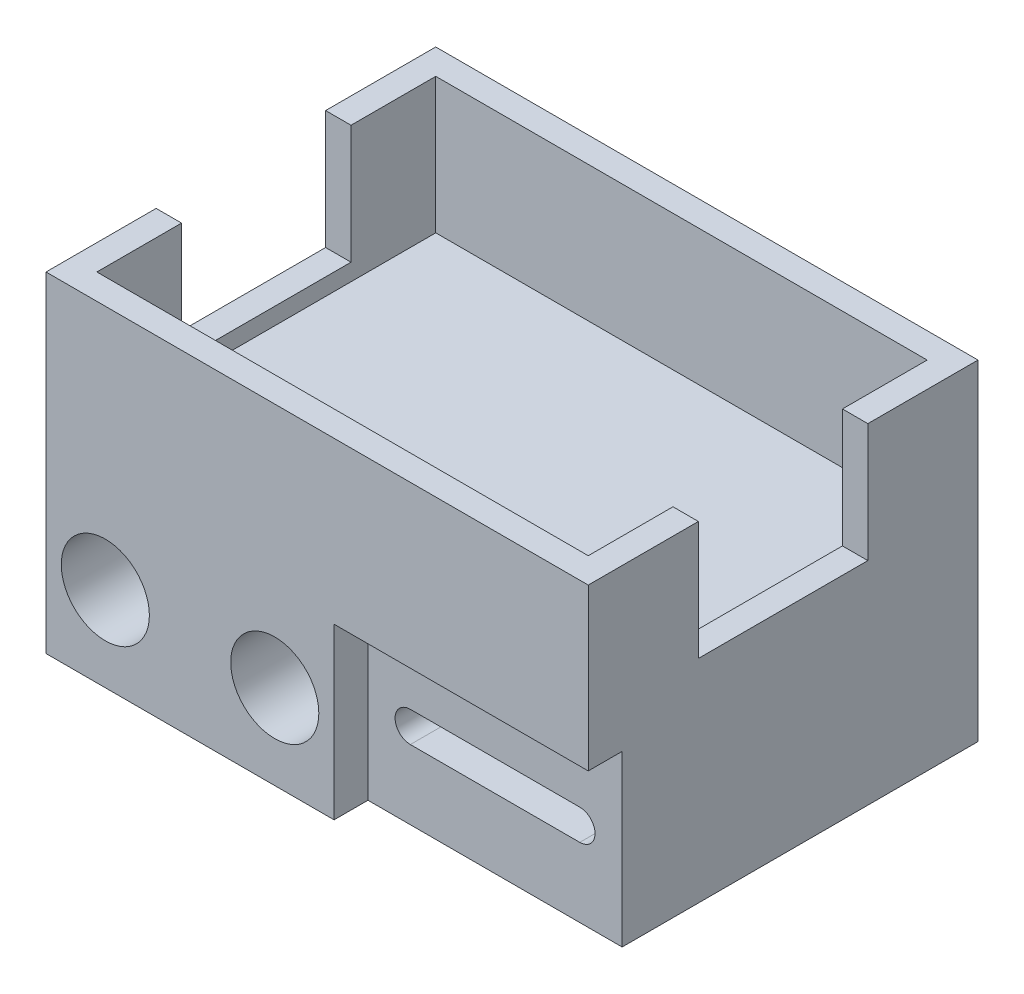
SolidWorks part; units mm, degrees
ref_plane "Front Plane" through (0, 0, 0) normal (0, 0, 1) x (1, 0, 0)
ref_plane "Top Plane" through (0, 0, 0) normal (0, 1, 0) x (1, 0, 0)
ref_plane "Right Plane" through (0, 0, 0) normal (1, 0, 0) x (0, 0, -1)
sketch "Sketch4" plane through (0, 0, 0) normal (0, 1, 0) x (1, 0, 0)
  line L1 (-16, -11.5) -> (16, -11.5)
  line L2 (-16, -11.5) -> (-16, 11.5)
  line L3 (-16, 11.5) -> (16, 11.5)
  line L4 (16, -11.5) -> (16, 11.5)
  line L5 (-16, -11.5) -> (16, 11.5) construction
  line L6 (-16, 11.5) -> (16, -11.5) construction
  point P0 (0, 0)
  dimension "D1" = 32
  dimension "D2" = 23
extrude "Boss-Extrude3" add sketch "Sketch4" along normal blind 9.5
sketch "Sketch5" plane through (0, 9.5, 0) normal (0, 1, 0) x (1, 0, 0)
  line L1 (-14.5, -10) -> (14.5, -10)
  line L2 (-14.5, -10) -> (-14.5, 10)
  line L3 (-14.5, 10) -> (14.5, 10)
  line L4 (14.5, -10) -> (14.5, 10)
  line L5 (-14.5, -10) -> (14.5, 10) construction
  line L6 (-14.5, 10) -> (14.5, -10) construction
  point P0 (0, 0)
  dimension "D1" = 29
  dimension "D2" = 20
extrude "Cut-Extrude2" cut sketch "Sketch5" against normal blind 8
sketch "Sketch7" plane through (16, 0, 0) normal (1, 0, 0) x (0, 0, -1)
  line L1 (-5, 2.5) -> (5, 2.5)
  line L2 (-5, 2.5) -> (-5, 9.5)
  line L3 (-5, 9.5) -> (5, 9.5)
  line L4 (5, 2.5) -> (5, 9.5)
  line L5 (-11.5, 9.5) -> (11.5, 9.5) construction
  point P6 (0, 9.5)
  point P8 (0, 9.5)
  dimension "D1" = 10
  dimension "D2" = 7
extrude "Cut-Extrude4" cut sketch "Sketch7" against normal through all
sketch "Sketch8" plane through (0, 0, 0) normal (0, -1, 0) x (-1, 0, 0)
  line L0 (-16, -9.5) -> (-1, -9.5)
  line L1 (-16, -11.5) -> (-16, 11.5) construction
  line L2 (-1, -9.5) -> (-1, -11.5)
  line L3 (16, -11.5) -> (-16, -11.5) construction
  line L4 (-1, -11.5) -> (16, -11.5)
  line L5 (16, -11.5) -> (16, 9.5)
  line L6 (16, 11.5) -> (16, -11.5) construction
  line L7 (16, 9.5) -> (1, 9.5)
  line L8 (1, 9.5) -> (1, 11.5)
  line L9 (-16, 11.5) -> (16, 11.5) construction
  line L10 (1, 11.5) -> (-16, 11.5)
  line L11 (-16, 11.5) -> (-16, -9.5)
  dimension "D1" = 2
  dimension "D2" = 15
extrude "Boss-Extrude4" add sketch "Sketch8" along normal blind 10
sketch "Sketch9" plane through (0, 0, -9.5) normal (0, 0, -1) x (-1, 0, 0)
  line L0 (3.5, -5) -> (13.5, -5) construction
  line L1 (3.5, -4.1) -> (13.5, -4.1)
  line L2 (3.5, -5.9) -> (13.5, -5.9)
  line L3 (16, -10) -> (1, -10) construction
  line L4 (16, -10) -> (16, 0) construction
  arc A0 (3.5, -4.1) -> (3.5, -5.9) centre (3.5, -5) ccw
  arc A1 (13.5, -5.9) -> (13.5, -4.1) centre (13.5, -5) ccw
  point P2 (8.5, -5)
  point P10 (8.5, -10)
  point P15 (16, -5)
  dimension "D1" = 1.8
  dimension "D2" = 10
ref_plane "Plane1" through (0, 0, 0) normal (0, 0, -1) x (-1, 0, 0)
extrude "Cut-Extrude5" cut sketch "Sketch9" against normal blind 5
sketch "Sketch10" plane through (0, -10, 0) normal (0, -1, 0) x (-1, 0, 0)
  line L0 (-16, 11.5) -> (-16, -9.5) construction
  line L1 (-1, -5.5) -> (-15, -5.5)
  line L2 (-1, -5.5) -> (-1, -2.5)
  line L3 (-1, -2.5) -> (-15, -2.5)
  line L4 (-15, -5.5) -> (-15, -2.5)
  line L5 (-1, -9.5) -> (-1, -11.5) construction
  line L6 (-16, -9.5) -> (-1, -9.5) construction
  line L7 (-5.5, 1) -> (-5.5, 15) [skipped]
  line L8 (-5.5, 1) -> (-2.5, 1) [skipped]
  line L9 (-2.5, 1) -> (-2.5, 15) [skipped]
  line L10 (-5.5, 15) -> (-2.5, 15) [skipped]
  line L11 (1, 5.5) -> (15, 5.5)
  line L12 (1, 5.5) -> (1, 2.5)
  line L13 (1, 2.5) -> (15, 2.5)
  line L14 (15, 5.5) -> (15, 2.5)
  line L15 (5.5, -1) -> (5.5, -15) [skipped]
  line L16 (5.5, -1) -> (2.5, -1) [skipped]
  line L17 (2.5, -1) -> (2.5, -15) [skipped]
  line L18 (5.5, -15) -> (2.5, -15) [skipped]
  line L19 (0, 0) -> (-1, -2.5) construction
  line L20 (10.725, 0) -> (-10.725, 0) construction
  point P10 (0.2818, 0)
  point P11 (0, 0)
  point P27 (-0.1187, 0)
  point P30 (2.5877, 0)
  point P32 (0, 0)
  dimension "D1" = 3
  dimension "D2" = 1
  dimension "D3" = 4
  dimension "D4" = 4
extrude "Cut-Extrude6" cut sketch "Sketch10" against normal offset from surface (7.9 mm away) 2 up to face at (-8.5, -4.1, -7) offset beyond the face yes
ref_axis "Axis1" through (0, 0, 0) along (0, -1, 0)
pattern_circular "CirPattern1" count 2 over 360 about axis through (0, 0, 0) along (0, -1, 0) of "Cut-Extrude5"
sketch "Sketch11" plane through (0, 0, -11.5) normal (0, 0, -1) x (-1, 0, 0)
  line L0 (-12.5, -5) -> (-2.5, -5) construction
  line L1 (1, -10) -> (-16, -10) construction
  circle A0 centre (-12.5, -5) radius 2.6
  circle A1 centre (-2.5, -5) radius 2.6
  arc A2 (3.5, -4.1) -> (3.5, -5.9) centre (3.5, -5) ccw construction
  point P6 (-7.5, -10)
  point P10 (2.6, -5)
  point P11 (-7.5, -5)
  dimension "D1" = 5.2
  dimension "D2" = 10
extrude "Cut-Extrude7" cut sketch "Sketch11" against normal blind 7
pattern_circular "CirPattern2" count 2 over 360 about axis through (0, 0, 0) along (0, -1, 0) of "Cut-Extrude7"
sketch "Sketch12" plane through (0, 0, 4.5) normal (0, 0, 1) x (1, 0, 0)
  circle A0 centre (-2.5, -5) radius 1.7
  circle A1 centre (-12.5, -5) radius 1.7
  dimension "D1" = 3.4
extrude "Cut-Extrude8" cut sketch "Sketch12" against normal up to surface (1 mm away)
sketch "Sketch13" plane through (0, 0, -4.5) normal (0, 0, -1) x (-1, 0, 0)
  circle A0 centre (-12.5, -5) radius 1.7
  circle A1 centre (-2.5, -5) radius 1.7
  dimension "D1" = 3.4
extrude "Cut-Extrude9" cut sketch "Sketch13" against normal up to surface (10 mm away)
